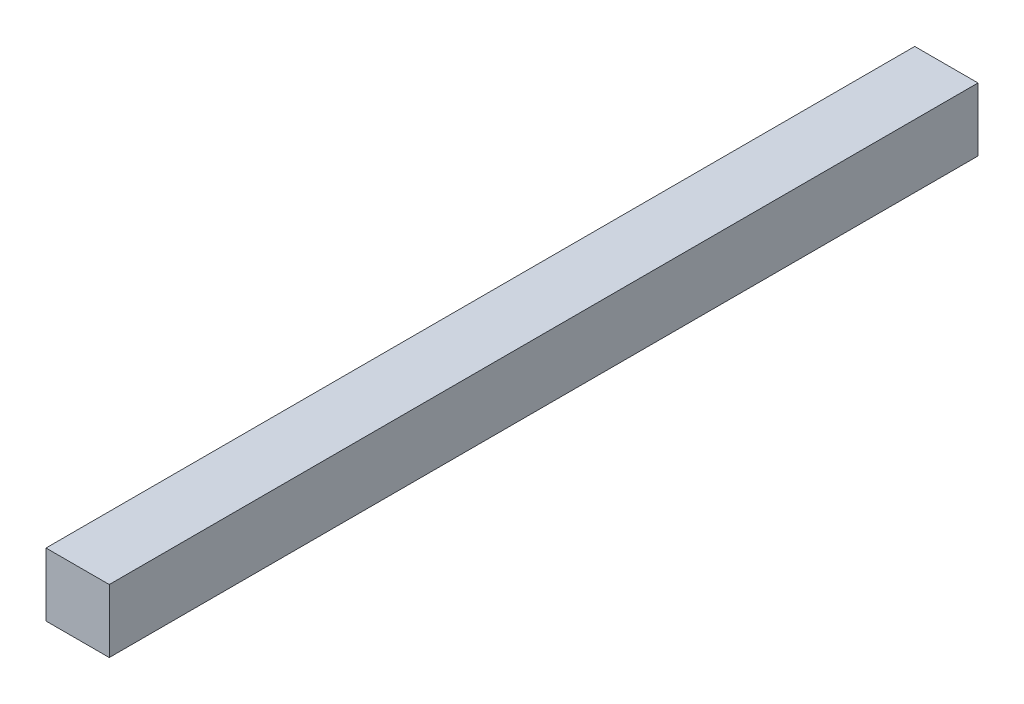
SolidWorks part; units mm, degrees
ref_plane "前视基准面" through (0, 0, 0) normal (0, 0, 1) x (1, 0, 0)
ref_plane "上视基准面" through (0, 0, 0) normal (0, 1, 0) x (1, 0, 0)
ref_plane "右视基准面" through (0, 0, 0) normal (1, 0, 0) x (0, 0, -1)
sketch "草图1" plane through (0, 0, 0) normal (0, 0, 1) x (1, 0, 0)
  line L1 (15, -15) -> (-15, -15)
  line L2 (15, -15) -> (15, 15)
  line L3 (15, 15) -> (-15, 15)
  line L4 (-15, -15) -> (-15, 15)
  line L5 (0, 15) -> (0, -15) construction
  line L6 (15, 0) -> (-15, 0) construction
  point P0 (0, 0)
  dimension "D1" = 30
extrude "凸台-拉伸1" add sketch "草图1" along normal mid plane 412
